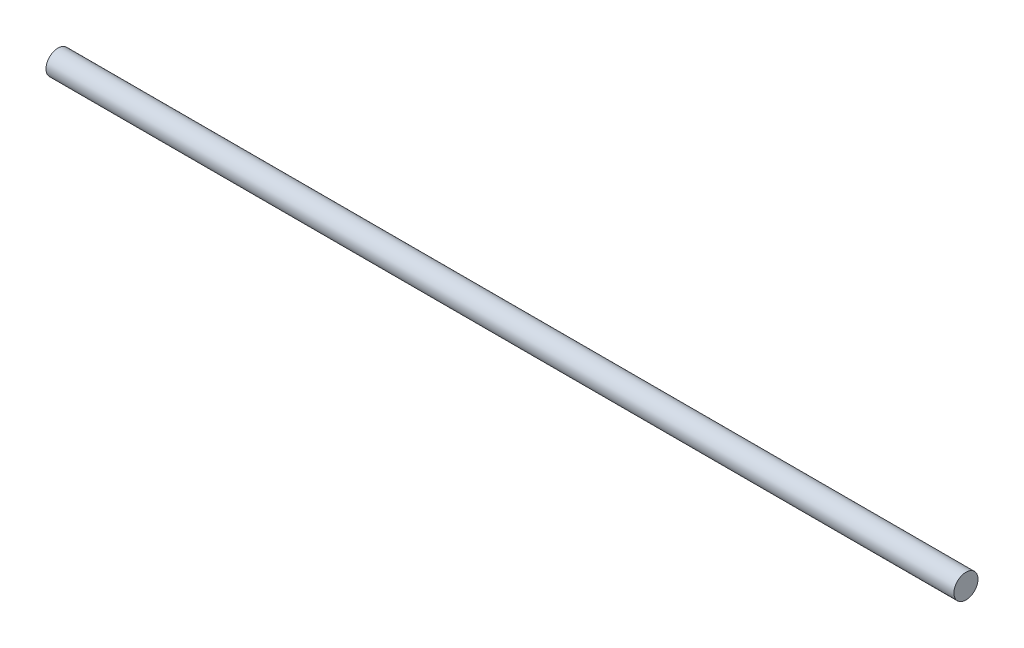
SolidWorks part; units mm, degrees
material "Alliage 1060"
ref_plane "Plan de face" through (0, 0, 0) normal (0, 0, 1) x (1, 0, 0)
ref_plane "Plan de dessus" through (0, 0, 0) normal (0, 1, 0) x (1, 0, 0)
ref_plane "Plan de droite" through (0, 0, 0) normal (1, 0, 0) x (0, 0, -1)
sketch "Esquisse1" plane through (0, 0, 0) normal (1, 0, 0) x (0, 0, -1)
  circle A0 centre (0, 0) radius 1.5
  dimension "D1" = 3
extrude "Extrusion1" add sketch "Esquisse1" along normal blind 60 and the other way blind 53
